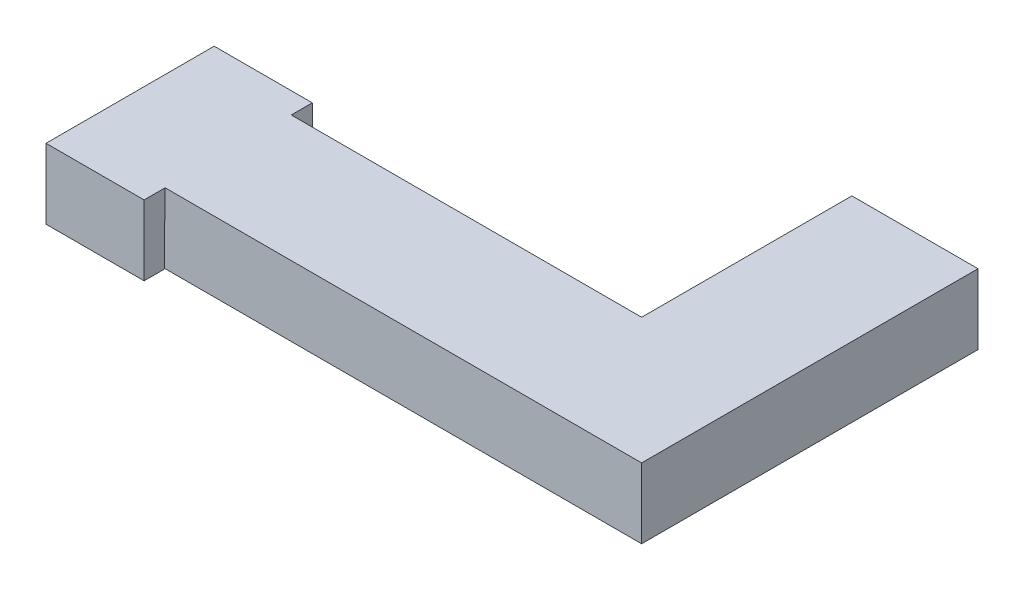
SolidWorks part; units mm, degrees
ref_plane "Front Plane" through (0, 0, 0) normal (0, 0, 1) x (1, 0, 0)
ref_plane "Top Plane" through (0, 0, 0) normal (0, 1, 0) x (1, 0, 0)
ref_plane "Right Plane" through (0, 0, 0) normal (1, 0, 0) x (0, 0, -1)
sketch "Sketch1" plane through (0, 0, 0) normal (0, 1, 0) x (1, 0, 0)
  line L0 (12.5, -4.5) -> (21.5, -4.5)
  line L1 (-12.5, -4.5) -> (12.5, -4.5)
  line L3 (-12.5, 4.5) -> (12.5, 4.5)
  line L5 (-12.5, -4.5) -> (12.5, 4.5) construction
  line L6 (-12.5, 4.5) -> (12.5, -4.5) construction
  line L7 (21.5, -4.5) -> (21.5, 19.5)
  line L8 (21.5, 19.5) -> (12.5, 19.5)
  line L9 (12.5, 19.5) -> (12.5, 4.5)
  line L10 (-12.5, 4.5) -> (-12.5, 6)
  line L11 (-12.5, 6) -> (-19.5, 6)
  line L12 (-19.5, 6) -> (-19.5, -6)
  line L13 (-19.5, -6) -> (-12.5, -6)
  line L14 (-12.5, -6) -> (-12.5, -4.5)
  point P0 (0, 0)
  dimension "D1" = 9
  dimension "D2" = 25
  dimension "D3" = 9
  dimension "D4" = 15
  dimension "D5" = 1.5
  dimension "D6" = 1.5
  dimension "D7" = 7
extrude "Boss-Extrude1" add sketch "Sketch1" along normal blind 2
sketch "Sketch2" plane through (0, 0, 0) normal (0, 1, 0) x (1, 0, 0)
  line L0 (-13.1507, 4.5) -> (12.5, 4.5)
  line L1 (12.5, 4.5) -> (12.5, 19.5)
  line L2 (12.5, 19.5) -> (14, 19.5)
  line L3 (21.5, 19.5) -> (12.5, 19.5) construction
  line L4 (14, 19.5) -> (14, 3)
  line L5 (14, 3) -> (-13.1507, 3)
  line L7 (-13.1507, 3) -> (-13.1507, 4.5)
  line L8 (20, 19.5) -> (20, -3)
  line L9 (20, -3) -> (-13.1507, -3)
  line L10 (-13.1507, -3) -> (-13.1507, -4.5)
  line L11 (-13.1507, -4.5) -> (21.5, -4.5)
  line L12 (21.5, -4.5) -> (21.5, 19.5)
  line L13 (21.5, 19.5) -> (20, 19.5)
  line L14 (-13.1507, 1) -> (16, 1)
  line L15 (16, 1) -> (16, 19.5)
  line L16 (16, 19.5) -> (18, 19.5)
  line L17 (18, 19.5) -> (18, -1)
  line L18 (18, -1) -> (-13.1507, -1)
  line L19 (-13.1507, -1) -> (-13.1507, 1)
  line L20 (-12.5, 6) -> (-19.5, 6)
  line L21 (-19.5, 6) -> (-19.5, 4.55)
  line L22 (-19.5, 6) -> (-19.5, -6) construction
  line L23 (-19.5, 4.55) -> (-12.5, 4.55)
  line L24 (-12.5, 4.5) -> (-12.5, 6) construction
  line L25 (-12.5, 4.55) -> (-12.5, 6)
  line L26 (-12.5, -4.55) -> (-19.5, -4.55)
  line L27 (-12.5, -6) -> (-12.5, -4.5) construction
  line L28 (-19.5, -4.55) -> (-19.5, -6)
  line L29 (-19.5, -6) -> (-12.5, -6)
  line L30 (-12.5, -6) -> (-12.5, -4.55)
  dimension "D1" = 1.5
  dimension "D2" = 2
  dimension "D3" = 2
  dimension "D4" = 2
  dimension "D5" = 2
  dimension "D6" = 1.45
  dimension "D7" = 1.45
extrude "Boss-Extrude2" add sketch "Sketch2" against normal blind 3
sketch "Sketch3" plane through (0, -3, 0) normal (0, -1, 0) x (1, 0, 0)
  line L0 (-13.1507, 3) -> (-13.1507, 4.5) construction
  line L1 (-13.1507, 3.55) -> (-19.5, 3.55)
  line L2 (-13.1507, 3.55) -> (-13.1507, 4.55)
  line L3 (-13.1507, 4.55) -> (-19.5, 4.55)
  line L4 (-19.5, 3.55) -> (-19.5, 4.55)
  line L5 (-13.1507, -4.5) -> (-13.1507, -3) construction
  line L6 (-13.1507, -3.55) -> (-19.5, -3.55)
  line L7 (-13.1507, -3.55) -> (-13.1507, -4.55)
  line L8 (-13.1507, -4.55) -> (-19.5, -4.55)
  line L9 (-19.5, -3.55) -> (-19.5, -4.55)
  dimension "D1" = 1
extrude "Boss-Extrude3" add sketch "Sketch3" against normal blind 2
